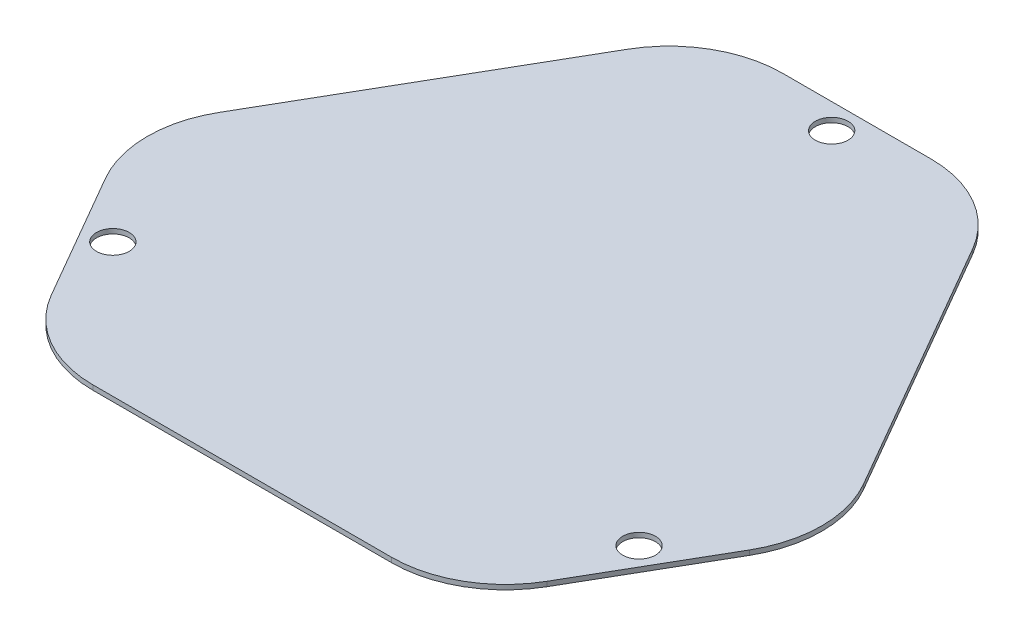
SolidWorks part; units mm, degrees
material "PC High Viscosity"
ref_plane "Front Plane" through (0, 0, 0) normal (0, 0, 1) x (1, 0, 0)
ref_plane "Top Plane" through (0, 0, 0) normal (0, 1, 0) x (1, 0, 0)
ref_plane "Right Plane" through (0, 0, 0) normal (1, 0, 0) x (0, 0, -1)
sketch "Sketch1" plane through (0, 0, 0) normal (0, 1, 0) x (1, 0, 0)
  line L0 (-534.2932, 43.4784) -> (-229.4932, -484.4507)
  line L1 (0, 407.1902) -> (-352.6371, -203.5951) construction
  line L2 (-352.6371, -203.5951) -> (352.6371, -203.5951) construction
  line L3 (352.6371, -203.5951) -> (0, 407.1902) construction
  line L4 (229.4932, -484.4507) -> (534.2932, 43.4784)
  line L5 (304.8, 440.9722) -> (-304.8, 440.9722)
  line L6 (0, 407.1902) -> (0, 440.9722) construction
  line L7 (-352.6371, -203.5951) -> (-381.8932, -220.4861) construction
  line L8 (352.6371, -203.5951) -> (381.8932, -220.4861) construction
  circle A0 centre (0, 0) radius 203.5951 construction
  circle A1 centre (352.6371, -203.5951) radius 21.082
  circle A2 centre (0, 407.1902) radius 21.082
  circle A3 centre (-352.6371, -203.5951) radius 21.082
  dimension "D2" = 42.164
  dimension "D1" = 705.2742
  dimension "D3" = 12.7
  dimension "D4" = 609.6
sketch "Sketch3" plane through (0, 0, 0) normal (0, 1, 0) x (1, 0, 0)
  line L0 (-534.2932, 43.4784) -> (-229.4932, -484.4507)
  line L1 (-229.4932, -484.4507) -> (229.4932, -484.4507)
  line L2 (229.4932, -484.4507) -> (534.2932, 43.4784)
  line L3 (534.2932, 43.4784) -> (304.8, 440.9722)
  line L4 (304.8, 440.9722) -> (-304.8, 440.9722)
  line L5 (-304.8, 440.9722) -> (-534.2932, 43.4784)
  circle A0 centre (-352.6371, -203.5951) radius 21.082 construction
  circle A1 centre (352.6371, -203.5951) radius 21.082 construction
  circle A2 centre (0, 407.1902) radius 21.082 construction
  circle A3 centre (-352.6371, -203.5951) radius 21.082
  circle A4 centre (352.6371, -203.5951) radius 21.082
  circle A5 centre (0, 407.1902) radius 21.082
extrude "Boss-Extrude1" add sketch "Sketch3" along normal blind 6.35
sketch "Sketch4" plane through (0, 6.35, 0) normal (0, 1, 0) x (1, 0, 0)
  line L0 (-187.4824, 440.9722) -> (-475.6344, -58.1216)
  line L1 (304.8, 440.9722) -> (-304.8, 440.9722) construction
  line L2 (-534.2932, 43.4784) -> (-229.4932, -484.4507) construction
  line L3 (-475.6344, -58.1216) -> (-534.2932, 43.4784)
  line L4 (-534.2932, 43.4784) -> (-304.8, 440.9722)
  line L5 (-304.8, 440.9722) -> (-187.4824, 440.9722)
  line L6 (304.8, 440.9722) -> (534.2932, 43.4784)
  line L7 (534.2932, 43.4784) -> (475.6344, -58.1216)
  line L8 (229.4932, -484.4507) -> (534.2932, 43.4784) construction
  line L9 (475.6344, -58.1216) -> (187.4824, 440.9722)
  line L10 (187.4824, 440.9722) -> (304.8, 440.9722)
  line L11 (229.4932, -484.4507) -> (-229.4932, -484.4507)
  line L12 (-229.4932, -484.4507) -> (-288.1519, -382.8507)
  line L13 (-288.1519, -382.8507) -> (288.1519, -382.8507)
  line L14 (288.1519, -382.8507) -> (229.4932, -484.4507)
  dimension "D1" = 101.6
extrude "Cut-Extrude1" cut sketch "Sketch4" against normal through all
fillet "Fillet1" radius 152.4 6 edges at (475.6344, 3.175, 58.1216) (187.4824, 3.175, -440.9722) (-187.4824, 3.175, -440.9722) (-288.1519, 3.175, 382.8507) (288.1519, 3.175, 382.8507) (-475.6344, 3.175, 58.1216)
sketch "Sketch5" plane through (0, 6.35, 0) normal (0, 1, 0) x (1, 0, 0)
  circle A0 centre (0, 407.1902) radius 21.971
  circle A1 centre (352.6371, -203.5951) radius 21.971
  circle A2 centre (-352.6371, -203.5951) radius 21.971
  dimension "D1" = 43.942
extrude "Cut-Extrude2" cut sketch "Sketch5" against normal through all
